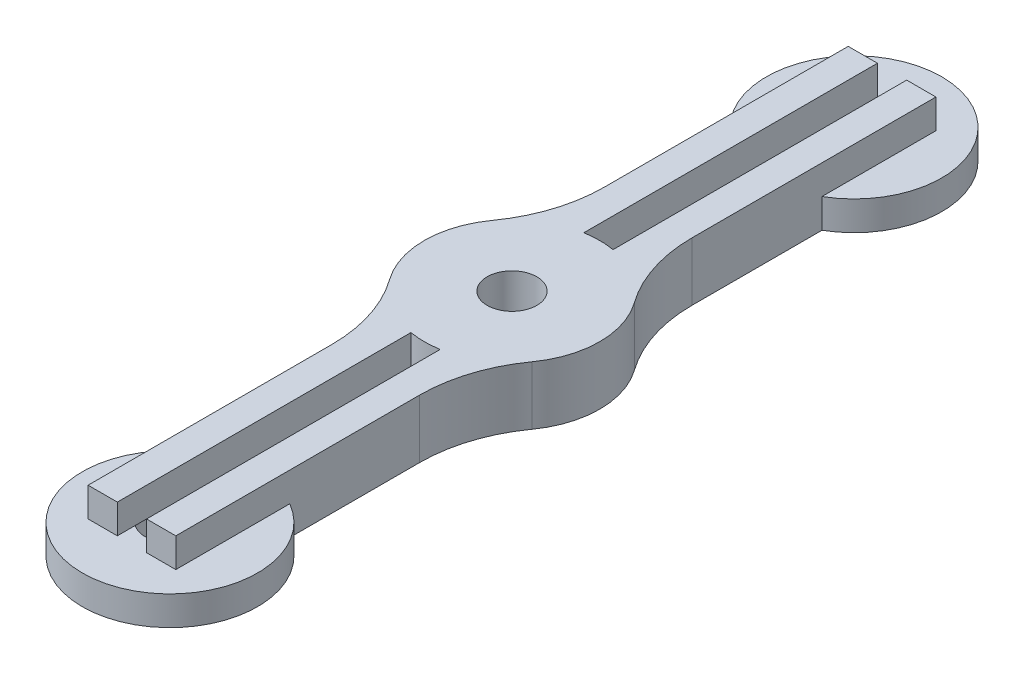
SolidWorks part; units mm, degrees
ref_plane "Front" through (0, 0, 0) normal (0, 0, 1) x (1, 0, 0)
ref_plane "Top" through (0, 0, 0) normal (0, 1, 0) x (1, 0, 0)
ref_plane "Right" through (0, 0, 0) normal (1, 0, 0) x (0, 0, -1)
sketch "Sketch1" plane through (0, 0, 0) normal (0, 1, 0) x (1, 0, 0)
  line L0 (0, -6) -> (0, -26)
  line L1 (-3, -26) -> (3, -26)
  line L2 (-3, -26) -> (-3, -5.1962)
  line L3 (3, -26) -> (3, -5.1962)
  circle A0 centre (0, 0) radius 1.7
  circle A1 centre (0, 0) radius 6
  circle A2 centre (0, -23.4) radius 6
  circle A4 centre (0, -23.4) radius 1.7
  point P9 (0, -26)
  point P14 (0, -32.6)
  dimension "D1" = 20
  dimension "D2" = 3.4
  dimension "D3" = 12
  dimension "D5" = 23.4
  dimension "D6" = 3.4
  dimension "D4" = 6
extrude "Boss-Extrude1" add sketch "Sketch1" along normal blind 2 contours A1 A0 | A1 L0 L1 L3 | A1 L2 L1 L0 | A2 L3 A1 L0 | A2 L0 A1 L2 | L2 A2 L3 L1
sketch "Sketch2" plane through (0, 2, 0) normal (0, 1, 0) x (1, 0, 0)
  line L0 (-3, -26) -> (-3, -5.1962)
  line L1 (-3, -5.1962) -> (-1, -5.1962)
  line L2 (-1, -5.1962) -> (-1, -26)
  line L3 (-3, -26) -> (3, -26) construction
  line L4 (-1, -26) -> (-3, -26)
  line L5 (3, -26) -> (1, -26)
  line L6 (1, -26) -> (1, -5.1962)
  line L7 (1, -5.1962) -> (3, -5.1962)
  line L8 (3, -5.1962) -> (3, -26)
  dimension "D1" = 2
  dimension "D2" = 2
extrude "Boss-Extrude2" add sketch "Sketch2" along normal blind 2
sketch "Sketch3" plane through (0, 2, 0) normal (0, 1, 0) x (1, 0, 0)
  circle A0 centre (0, 0) radius 1.7
  circle A1 centre (0, 0) radius 6
extrude "Boss-Extrude3" add sketch "Sketch3" along normal blind 2
fillet "Fillet1" radius 10 2 edges at (3, 2, 5.1962) (-3, 2, 5.1962)
mirror "Mirror1" about plane through (0, 0, 0) normal (0, 0, 1) of "Boss-Extrude2", "Boss-Extrude1"
fillet "Fillet2" radius 10 2 edges at (-3, 2, -5.1962) (3, 2, -5.1962)
